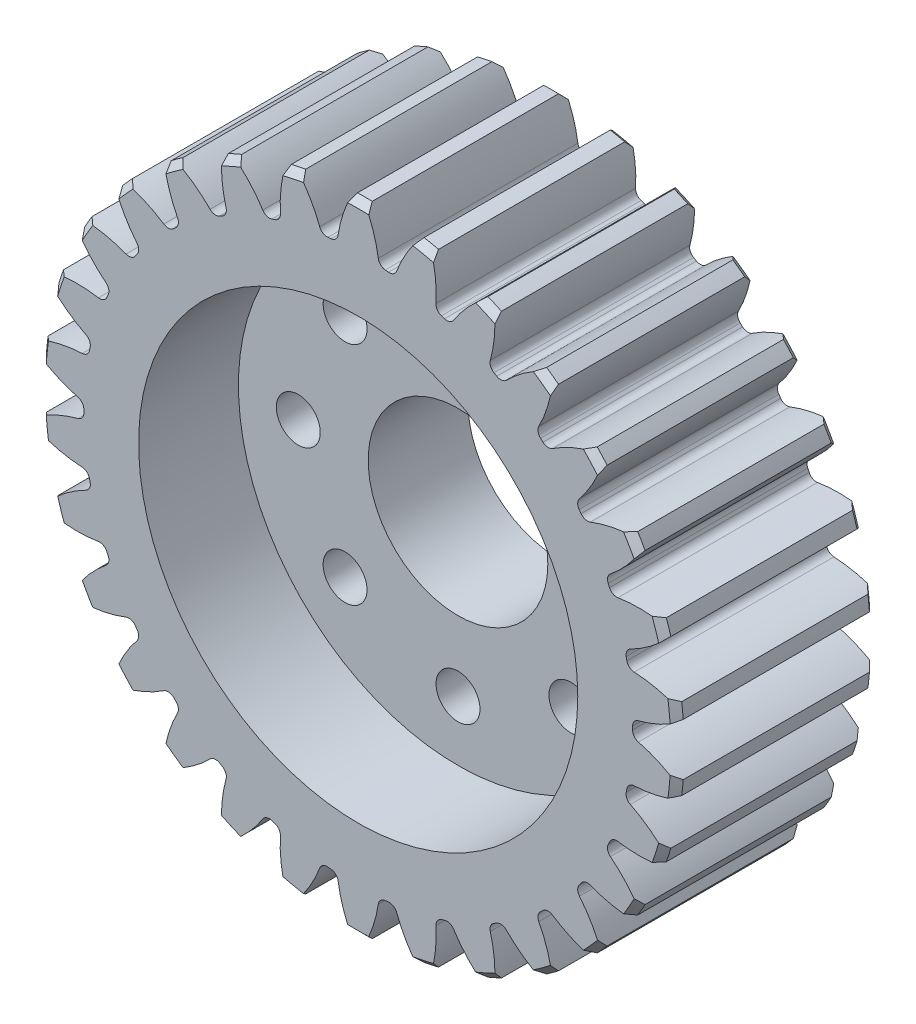
SolidWorks part; units mm, degrees
ref_plane "Front Plane" through (0, 0, 0) normal (0, 0, 1) x (1, 0, 0)
ref_plane "Top Plane" through (0, 0, 0) normal (0, 1, 0) x (1, 0, 0)
ref_plane "Right Plane" through (0, 0, 0) normal (1, 0, 0) x (0, 0, -1)
sketch "Sketch1" plane through (0, 0, 0) normal (0, 0, 1) x (1, 0, 0)
  line L0 (0, 0) -> (0, 15) construction
  line L1 (-4.8209, 16.7547) -> (4.8209, 13.2453) construction
  circle A0 centre (0, 0) radius 13.75 construction
  circle A1 centre (0, 0) radius 16 construction
  circle A2 centre (0, 0) radius 15 construction
  circle A3 centre (0, 0) radius 14.0954 construction
  circle A4 centre (0, 0) radius 12.5 construction
  circle A5 centre (0, 0) radius 4 construction
  point P8 (0.5, 0)
  point P13 (15, 0)
  dimension "OD" = 32
  dimension "Root Diameter" = 27.5
  dimension "Gear Pitch Diameter" = 30
  dimension "Base Diameter" = 28.1908
  dimension "Hub Diameter" = 25
  dimension "For Shaft Diameter" = 8
  dimension "Pressure Angle" = 20
  dimension "Number of Teeth" = 30
  dimension "Module" = 1
sketch "Sketch2" plane through (0, 0, 0) normal (1, 0, 0) x (0, 0, -1)
  line L0 (-10, 0) -> (10, 0) construction
  line L1 (10, 16) -> (10, -16) construction
  line L2 (0, -12.5) -> (-10, -12.5) construction
  line L3 (-10, 16) -> (10, 16) construction
  line L8 (-10, -12.5) -> (-10, 12.5) construction
  point P4 (0, 16)
  point P5 (-5, 0)
  dimension "Overall Width" = 20
  dimension "Hub Width" = 10
  dimension "Approx Set Screw Positon" = 5
  dimension "Face Width" = 10
sketch "Sketch3" plane through (0, 0, 0) normal (0, 0, 1) x (1, 0, 0)
  circle A0 centre (0, 0) radius 16
  circle A1 centre (0, 0) radius 16 construction
extrude "Boss-Extrude1" add sketch "Sketch3" against normal up to vertex (10 mm away) and the other way up to vertex (10 mm away) up to point (0, 0, -10) other way up to point (0, 0, 10)
sketch "Sketch5" plane through (0, 0, 0) normal (1, 0, 0) x (0, 0, -1)
  line L1 (0, 12.5) -> (-10, 12.5)
  line L2 (0, 12.5) -> (0, 16)
  line L3 (0, 16) -> (-10, 16)
  line L4 (-10, 12.5) -> (-10, 16)
  line L5 (-10, 0) -> (10, 0)
  line L6 (-10, 0) -> (-10, 4)
  line L7 (-10, 4) -> (10, 4)
  line L8 (10, 0) -> (10, 4)
  point P5 (0, 12.5)
  point P12 (0, 4)
revolve "Cut-Revolve1" cut sketch "Sketch5" angle 360 about L0
fillet "Fillet2" radius 0.3355 1 edges at (0, -12.5, 0)
chamfer "Chamfer1" distance 0.3355 angle 45 5 edges at (0, -4, -10) (0, -16, 0) (16, 0, -10) (0, -4, 10) (0, -12.5, 10)
sketch "Sketch4" plane through (0, 0, 0) normal (0, 0, 1) x (1, 0, 0)
  line L0 (13.7444, 0.3927) -> (13.7444, -0.3927)
  arc A3 (15.9467, 1.3054) -> (15.9467, -1.3054) centre (0, 0) cw
  circle A4 centre (0, 0) radius 16 construction
  arc A5 (13.7444, 0.3927) -> (15.9467, 1.3054) centre (12.3619, 6.8422) ccw
  circle A8 centre (0, 0) radius 13.75 construction
  arc A9 (13.7444, -0.3927) -> (15.9467, -1.3054) centre (12.3619, -6.8422) cw
  spline S0 degree 4 poles (14.0855, 0.5278) (14.0885, 0.528) (14.0969, 0.5285) (14.1128, 0.5299) (14.1387, 0.5328) (14.1717, 0.5373) (14.2142, 0.5441) (14.2642, 0.5535) (14.319, 0.5651) (14.3785, 0.5792) (14.4378, 0.5946) (14.4967, 0.6111) (14.5554, 0.6286) (14.6262, 0.6511) (14.7109, 0.6798) (14.8096, 0.716) (14.9211, 0.76) (15.0342, 0.8081) (15.1451, 0.8581) (15.2566, 0.9116) (15.3642, 0.9655) (15.4753, 1.0247) (15.5776, 1.0809) (15.6916, 1.1472) (15.7833, 1.2018) (15.9036, 1.2774) (15.9744, 1.3231) (16.0571, 1.3779) (16.0936, 1.4029) (16.1161, 1.4183) knots 0 0 0 0 0 0.005377 0.015084 0.028532 0.04661 0.064855 0.092111 0.119476 0.146842 0.174209 0.201575 0.228941 0.256307 0.307035 0.361767 0.4165 0.471232 0.525964 0.580697 0.635429 0.690161 0.744894 0.799626 0.854358 0.909091 0.954545 1 1 1 1 1 construction
  spline S1 degree 4 poles (14.0855, 0.5278) (14.0885, 0.528) (14.0969, 0.5285) (14.1128, 0.5299) (14.1387, 0.5328) (14.1717, 0.5373) (14.2142, 0.5441) (14.2642, 0.5535) (14.319, 0.5651) (14.3785, 0.5792) (14.4378, 0.5946) (14.4967, 0.6111) (14.5554, 0.6286) (14.6262, 0.6511) (14.7109, 0.6798) (14.8096, 0.716) (14.9211, 0.76) (15.0342, 0.8081) (15.1451, 0.8581) (15.2566, 0.9116) (15.3642, 0.9655) (15.4753, 1.0247) (15.5776, 1.0809) (15.6916, 1.1472) (15.7833, 1.2018) (15.8775, 1.261) (15.9233, 1.2902) (15.9467, 1.3054) knots 0 0 0 0 0 0.005377 0.015084 0.028532 0.04661 0.064855 0.092111 0.119476 0.146842 0.174209 0.201575 0.228941 0.256307 0.307035 0.361767 0.4165 0.471232 0.525964 0.580697 0.635429 0.690161 0.744894 0.799626 0.854358 0.909091 0.909091 0.909091 0.909091 0.909091 construction
  spline S2 degree 4 poles (14.0855, -0.5278) (14.0885, -0.528) (14.0969, -0.5285) (14.1128, -0.5299) (14.1387, -0.5328) (14.1717, -0.5373) (14.2142, -0.5441) (14.2642, -0.5535) (14.319, -0.5651) (14.3785, -0.5792) (14.4378, -0.5946) (14.4967, -0.6111) (14.5554, -0.6286) (14.6262, -0.6511) (14.7109, -0.6798) (14.8096, -0.716) (14.9211, -0.76) (15.0342, -0.8081) (15.1451, -0.8581) (15.2566, -0.9116) (15.3642, -0.9655) (15.4753, -1.0247) (15.5776, -1.0809) (15.6916, -1.1472) (15.7833, -1.2018) (15.9036, -1.2774) (15.9744, -1.3231) (16.0571, -1.3779) (16.0936, -1.4029) (16.1161, -1.4183) knots 0 0 0 0 0 0.005377 0.015084 0.028532 0.04661 0.064855 0.092111 0.119476 0.146842 0.174209 0.201575 0.228941 0.256307 0.307035 0.361767 0.4165 0.471232 0.525964 0.580697 0.635429 0.690161 0.744894 0.799626 0.854358 0.909091 0.954545 1 1 1 1 1 construction
  spline S3 degree 4 poles (14.0855, -0.5278) (14.0885, -0.528) (14.0969, -0.5285) (14.1128, -0.5299) (14.1387, -0.5328) (14.1717, -0.5373) (14.2142, -0.5441) (14.2642, -0.5535) (14.319, -0.5651) (14.3785, -0.5792) (14.4378, -0.5946) (14.4967, -0.6111) (14.5554, -0.6286) (14.6262, -0.6511) (14.7109, -0.6798) (14.8096, -0.716) (14.9211, -0.76) (15.0342, -0.8081) (15.1451, -0.8581) (15.2566, -0.9116) (15.3642, -0.9655) (15.4753, -1.0247) (15.5776, -1.0809) (15.6916, -1.1472) (15.7833, -1.2018) (15.8775, -1.261) (15.9233, -1.2902) (15.9467, -1.3054) knots 0 0 0 0 0 0.005377 0.015084 0.028532 0.04661 0.064855 0.092111 0.119476 0.146842 0.174209 0.201575 0.228941 0.256307 0.307035 0.361767 0.4165 0.471232 0.525964 0.580697 0.635429 0.690161 0.744894 0.799626 0.854358 0.909091 0.909091 0.909091 0.909091 0.909091 construction
  dimension "D1" = 0.7854
extrude "Cut-Extrude1" cut sketch "Sketch4" against normal through all both and the other way through all
fillet "Fillet1" radius 0.3927 2 edges at (13.7444, 0.3927, -5) (13.7444, -0.3927, -5)
pattern_circular "CirPattern1" count 30 over 360 about axis through (0, 0, 0) along (0, 0, 1) of "Cut-Extrude1", "Fillet1"
split "Split1" trim tools "Front Plane" bodies to split 106 resulting bodies 155
sketch "Sketch6" plane through (0, 0, 0) normal (0, 0, 1) x (1, 0, 0)
  circle A0 centre (0, 0) radius 4.3355 construction
  circle A1 centre (0, 0) radius 4.3355
extrude "Boss-Extrude2" [suppressed] add sketch "Sketch6" against normal up to surface (10 mm away)
hole_wizard "M2 Clearance Hole1" positions "Sketch8" profile "Sketch9" hole size "M2" standard "ANSI Metric" end condition through all
sketch "Sketch8" plane through (0, 0, 0) normal (0, 0, 1) x (1, 0, 0)
  circle A0 centre (0, 0) radius 8 construction
  circle A1 centre (0, 0) radius 8 construction
  circle A2 centre (0, 0) radius 8 construction
  circle A3 centre (0, 0) radius 8 construction
  circle A4 centre (0, 0) radius 8 construction
  circle A5 centre (0, 0) radius 8 construction
  circle A6 centre (0, 0) radius 8 construction
  circle A7 centre (0, 0) radius 8 construction
  point P5 (-8, 0)
  point P13 (-5.6569, 5.6569)
  point P15 (0, 8)
  point P17 (5.6569, 5.6569)
  point P19 (8, 0)
  point P21 (5.6569, -5.6569)
  point P23 (0, -8)
  point P25 (-5.6569, -5.6569)
  dimension "D1" = 16
  dimension "D2" = 8
sketch "Sketch9" plane through (-5.6569, -5.6569, 0) normal (1, 0, 0) x (0, -1, 0)
  line L0 (0, 0) -> (0, 10)
  line L1 (0, 10) -> (1.1, 10)
  line L2 (1.1, 10) -> (1.1, 0.025)
  line L3 (1.1, 0.025) -> (1.125, 0)
  line L5 (1.125, 0) -> (0, 0)
  line L6 (-1.1, 0.025) -> (-1.125, 0) construction
  line L11 (0, -6.35) -> (0, 107.95) construction
  dimension "Thru Hole Dia." = 2.2
  dimension "Thru Hole Depth" = 10
  dimension "Near C'Sink Dia." = 2.25
  dimension "Near C'Sink Angle" = 90
sketch "Sketch7" plane through (0, 0, 0) normal (0, 0, 1) x (1, 0, 0)
  circle A0 centre (0, 0) radius 15
  dimension "D1" = 30
surface "Surface-Extrude1" sketch "Sketch7" parameters "D1"=10
sketch "Sketch10" plane through (0, 0, 0) normal (0, 0, 1) x (1, 0, 0)
  circle A0 centre (0, 0) radius 4.5
  dimension "D1" = 9
extrude "Cut-Extrude2" cut sketch "Sketch10" against normal through all both and the other way through all
ref_plane "Plane1" through (7.4192, 11.9254, -10) normal (0, 0, 1) x (1, 0, 0)
sketch "Sketch11" plane through (7.4192, 11.9254, -10) normal (0, 0, 1) x (1, 0, 0)
  circle A0 centre (-7.4192, -11.9254) radius 11
  circle A1 centre (-7.4192, -11.9254) radius 11 construction
extrude "Cut-Extrude3" cut sketch "Sketch11" against normal blind 5 from surface at 10 starting at face at (4.5, 0, 0)
equation "\"Number of Teeth\"= 30"
equation "\"Module\"= 1"
equation "\"Diametral Pitch\"= 1 / \"Module\""
equation "\"Dedendum\"= 1.25 / \"Diametral Pitch\""
equation "\"Pitch Diameter\"= \"Module\" * \"Number of Teeth\""
equation "\"Root Diameter\"= \"Pitch Diameter\" - ( 2 * \"Dedendum\" )"
equation "\"Root Diameter@Sketch1\"=\"Root Diameter\""
equation "\"OD@Sketch1\" = \"Outside Diameter\""
equation "\"D1@CirPattern1\"=\"Number of Teeth\""
equation "\"Pressure Angle\"=20"
equation "\"Base Diameter\"= \"Pitch Diameter\" * cos ( \"Pressure Angle\" )"
equation "\"Outside Diameter\"= ( \"Number of Teeth\" + 2 ) / \"Diametral Pitch\""
equation "\"Pitch Angle\"= 360deg / \"Number of Teeth\""
equation "\"Alpha\"= sqr ( \"Pitch Diameter\" ^ 2 - \"Base Diameter\" ^ 2 ) / \"Base Diameter\" * 180 / PI - \"Pressure Angle\""
equation "\"Beta\"= ( \"Pitch Angle\" / 4 - \"Alpha\" )"
equation "\"Phi\"= sqr ( ( \"Outside Diameter\" / 2 ) ^ 2 - ( \"Base Diameter\" / 2 ) ^ 2 ) / ( \"Base Diameter\" / 2 )"
equation "\"Addendum\"= 1 / \"Diametral Pitch\""
equation "\"WorkingDepth\"= 2 / \"Diametral Pitch\""
equation "\"WholeDepth\"= 2.25 / \"Diametral Pitch\""
equation "\"Clearance\"= 0.25 / \"Diametral Pitch\""
equation "\"ToothThickness\"= ( pi * 2 ) / \"Diametral Pitch\""
equation "\"CircularPitch\"= pi / \"Diametral Pitch\""
equation "\"Number of Teeth@Sketch1\"=\"Number of Teeth\""
equation "\"Module@Sketch1\"=\"Module\""
equation "\"Pressure Angle@Sketch1\"=\"Pressure Angle\""
equation "\"Gear Pitch Diameter@Sketch1\"=\"Pitch Diameter\""
equation "\"Base Diameter@Sketch1\"=\"Base Diameter\""
equation "\"Fillet\"= \"Clearance\" * cos ( \"Pressure Angle\" ) * tan ( ( 90 + \"Pressure Angle\" ) / 2 )"
equation "\"D1@Fillet2\"=\"Fillet\""
equation "\"Approx Set Screw Positon@Sketch2\" = \"Hub Width@Sketch2\" / 2"
equation "\"D2\"= \"Fillet\" * 2"
equation "\"D1@Chamfer1\"=\"Fillet\""
equation "\"D1@Sketch4\"=\"CircularPitch\"*0.25"
equation "\"D1@Fillet1\"=\"CircularPitch\"*0.125"
